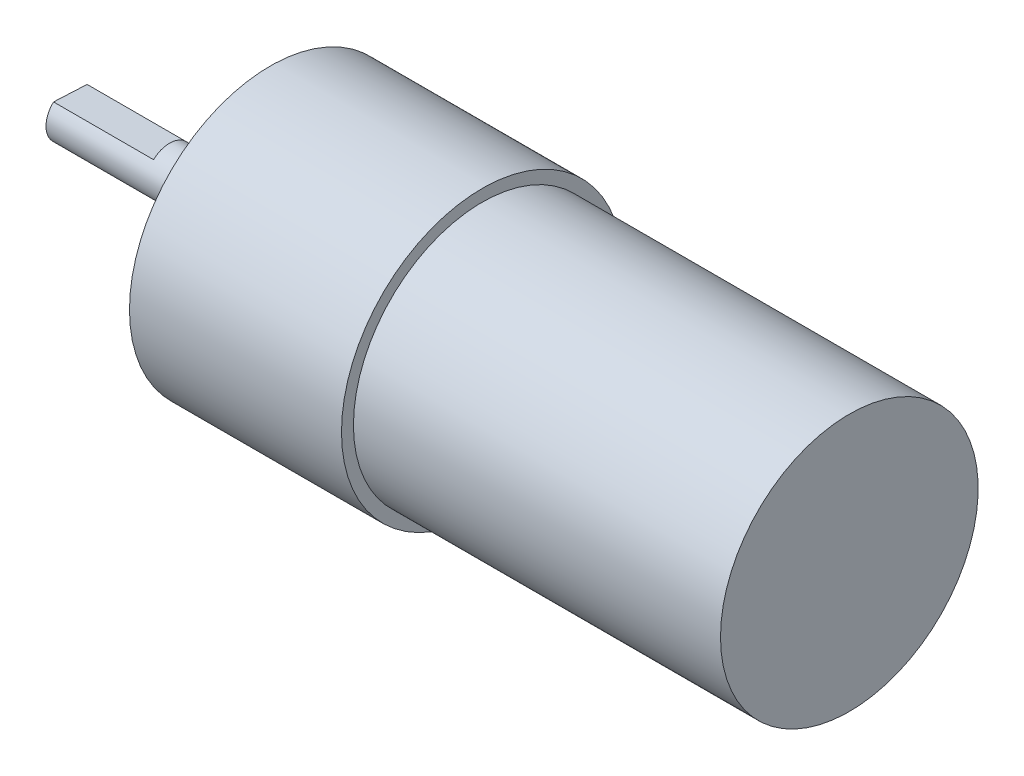
SolidWorks part; units mm, degrees
ref_plane "Front Plane" through (0, 0, 0) normal (0, 0, 1) x (1, 0, 0)
ref_plane "Top Plane" through (0, 0, 0) normal (0, 1, 0) x (1, 0, 0)
ref_plane "Right Plane" through (0, 0, 0) normal (1, 0, 0) x (0, 0, -1)
sketch "Sketch2" plane through (0, 0, 0) normal (0, 1, 0) x (1, 0, 0)
  line L0 (-41.7244, 0) -> (24.5556, 0)
  line L1 (24.5556, 0) -> (24.5556, 10.95)
  line L2 (24.5556, 10.95) -> (-6.6444, 10.95)
  line L3 (-6.6444, 10.95) -> (-6.6444, 11.965)
  line L4 (-6.6444, 11.965) -> (-24.6644, 11.965)
  line L5 (-24.6644, 11.965) -> (-24.6644, 4.97)
  line L6 (-24.6644, 4.97) -> (-27.4944, 4.97)
  line L7 (-27.4944, 4.97) -> (-27.4944, 3.965)
  line L8 (-27.4944, 3.965) -> (-28.2244, 3.965)
  line L9 (-28.2244, 3.965) -> (-28.2244, 3.2)
  line L10 (-28.8244, 2) -> (-41.7244, 2)
  line L11 (-41.7244, 2) -> (-41.7244, 0)
  line L12 (-28.2244, 3.2) -> (-28.8244, 3.2)
  line L13 (-28.8244, 3.2) -> (-28.8244, 2)
  dimension "D1" = 10.95
  dimension "D2" = 11.965
  dimension "D3" = 4.97
  dimension "D4" = 3.965
  dimension "D5" = 3.2
  dimension "D6" = 2
  dimension "D7" = 31.2
  dimension "D8" = 18.02
  dimension "D9" = 2.83
  dimension "D10" = 0.73
  dimension "D11" = 0.6
  dimension "D12" = 12.9
  dimension "D13" = 24.5556
revolve "Revolve1" add sketch "Sketch2" angle 360 about L0
sketch "Sketch3" plane through (-41.7244, 0, 0) normal (-1, 0, 0) x (0, 0, 1)
  line L0 (-1.4939, 1.3297) -> (1.3593, 1.467)
  circle A1 centre (0, 0) radius 2 construction
  circle A2 centre (0, 0) radius 2
  arc A3 (1.3593, 1.467) -> (-1.4939, 1.3297) centre (0, 0) ccw
  dimension "D2" = 1.4
  dimension "D3" = 1.3593
  dimension "D1" = 0
extrude "Cut-Extrude1" cut sketch "Sketch3" against normal blind 8.5
sketch "Sketch4" plane through (-24.6644, 0, 0) normal (-1, 0, 0) x (0, 0, 1)
  circle A0 centre (-2.529, 8.041) radius 1
  circle A1 centre (0, 0) radius 4.97 construction
  circle A2 centre (8.2282, -1.8303) radius 1
  circle A3 centre (-5.6992, -6.2107) radius 1
  circle A5 centre (0, 0) radius 9.465
  circle A6 centre (0, 0) radius 9.465
  point P7 (0, 0)
  dimension "D1" = 2
  dimension "D2" = 2
  dimension "D3" = 2
  dimension "D4" = 14.6
  dimension "D5" = 14.6
  dimension "D6" = 14.6
  dimension "D7" = 2.5
  dimension "D8" = 8.2282
  dimension "D9" = 5.6992
  dimension "D10" = 120
extrude "Cut-Extrude2" cut sketch "Sketch4" against normal blind 10 contours A0 | A3 | A2
